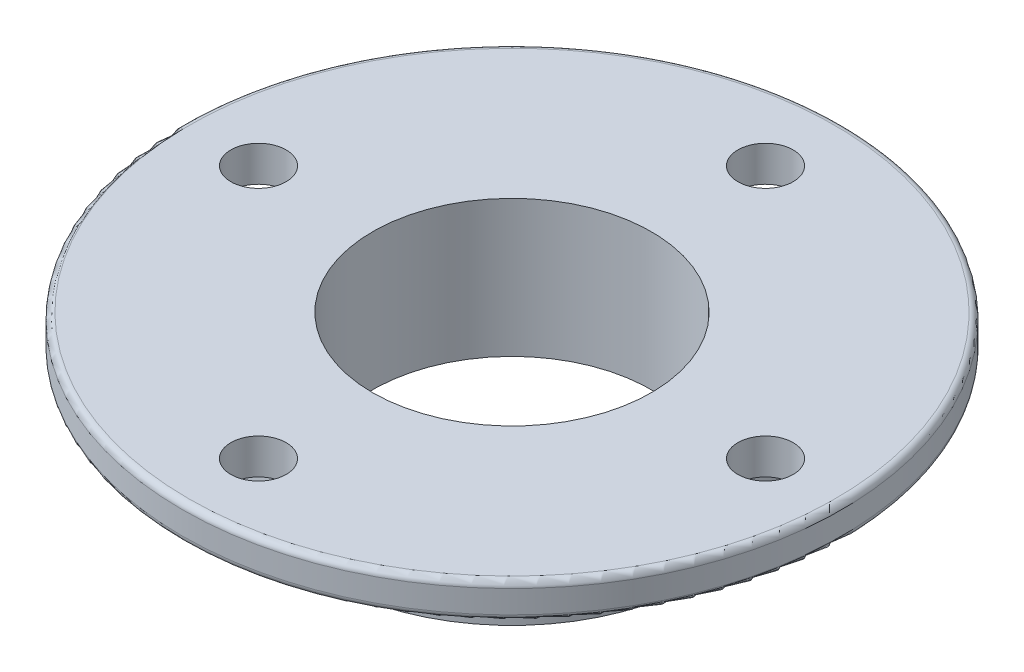
SolidWorks part; units mm, degrees
ref_plane "Front" through (0, 0, 0) normal (0, 0, 1) x (1, 0, 0)
ref_plane "Top" through (0, 0, 0) normal (0, 1, 0) x (1, 0, 0)
ref_plane "Right" through (0, 0, 0) normal (1, 0, 0) x (0, 0, -1)
sketch "Sketch1" plane through (0, 0, 0) normal (0, 1, 0) x (1, 0, 0)
  circle A0 centre (0, 0) radius 5.5
  circle A1 centre (0, 0) radius 7.5
  dimension "D1" = 11
  dimension "D2" = 15
extrude "Boss-Extrude1" add sketch "Sketch1" along normal blind 4
ref_plane "Plane1" through (0, 4, 0) normal (0, 1, 0) x (1, 0, 0)
sketch "Sketch2" plane through (0, 4, 0) normal (0, 1, 0) x (1, 0, 0)
  circle A0 centre (0, 0) radius 13
  circle A1 centre (0, 0) radius 5.5
  circle A2 centre (0, 0) radius 5.5 construction
  dimension "D2" = 26
extrude "Boss-Extrude2" add sketch "Sketch2" along normal blind 1.4
sketch "Sketch3" plane through (0, 5.4, 0) normal (0, 1, 0) x (1, 0, 0)
  line L0 (0, 0) -> (0, 13) construction
  circle A0 centre (0, 0) radius 13 construction
  circle A1 centre (0, 10) radius 1.09
  dimension "D1" = 2.18
  dimension "D2" = 10
extrude "Cut-Extrude1" cut sketch "Sketch3" against normal through all
pattern_circular "CirPattern1" count 4 over 360 about axis through (0, 0, 0) along (0, 1, 0) of "Cut-Extrude1"
fillet "Fillet1" radius 0.25 2 edges at (0, 5.4, 13) (0, 4, 13)
